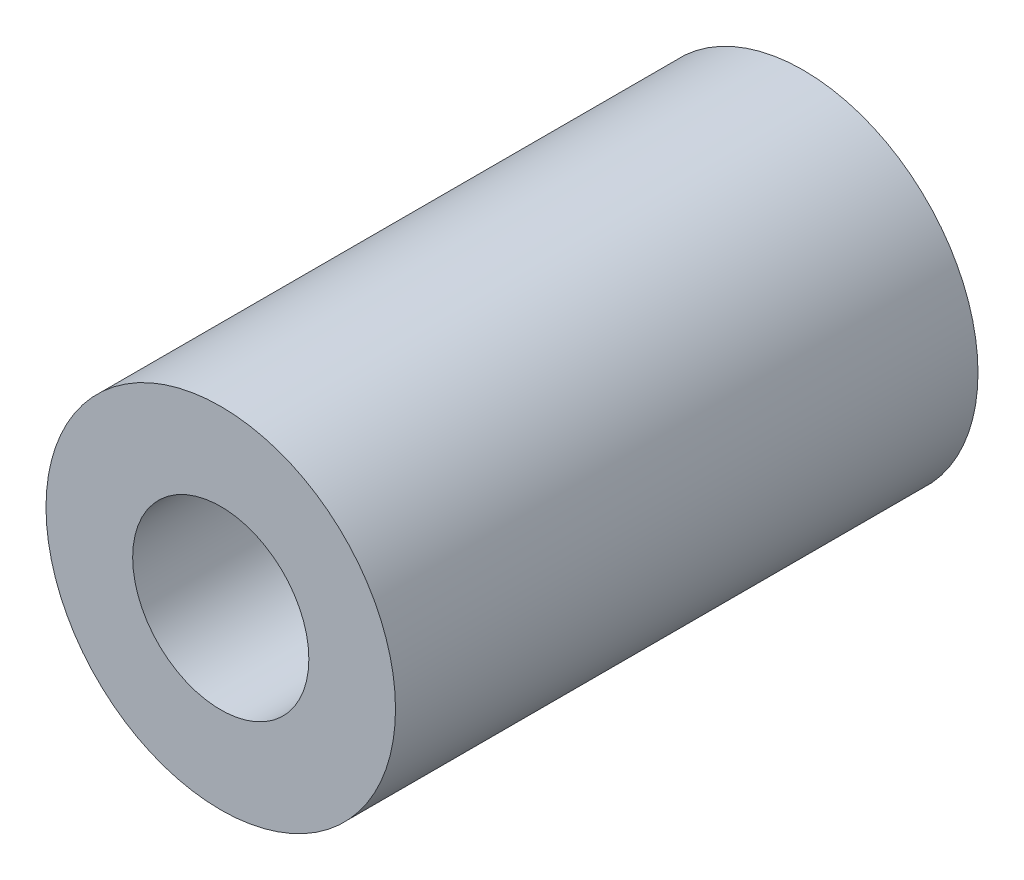
SolidWorks part; units mm, degrees
ref_plane "Front Plane" through (0, 0, 0) normal (0, 0, 1) x (1, 0, 0)
ref_plane "Top Plane" through (0, 0, 0) normal (0, 1, 0) x (1, 0, 0)
ref_plane "Right Plane" through (0, 0, 0) normal (1, 0, 0) x (0, 0, -1)
sketch "Sketch1" plane through (0, 0, 0) normal (0, 0, 1) x (1, 0, 0)
  circle A0 centre (0, 0) radius 6
  dimension "D1" = 12
extrude "Boss-Extrude1" add sketch "Sketch1" along normal blind 20
sketch "Sketch2" plane through (0, 0, 0) normal (0, 0, -1) x (-1, 0, 0)
  circle A0 centre (0, 0) radius 4.025
  dimension "D1" = 8.05
extrude "Cut-Extrude1" cut sketch "Sketch2" against normal blind 6
sketch "Sketch3" plane through (0, 0, 20) normal (0, 0, 1) x (1, 0, 0)
  circle A0 centre (0, 0) radius 3.025
  dimension "D1" = 6.05
extrude "Cut-Extrude2" cut sketch "Sketch3" against normal blind 15
